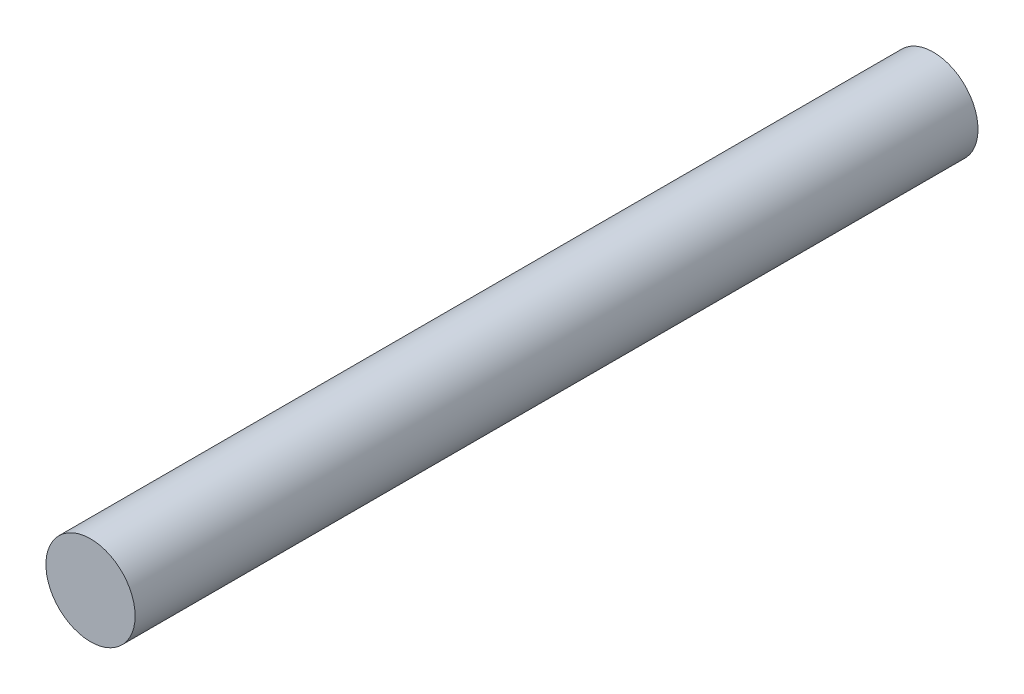
SolidWorks part; units mm, degrees
ref_plane "Alzado" through (0, 0, 0) normal (0, 0, 1) x (1, 0, 0)
ref_plane "Planta" through (0, 0, 0) normal (0, 1, 0) x (1, 0, 0)
ref_plane "Vista lateral" through (0, 0, 0) normal (1, 0, 0) x (0, 0, -1)
sketch "Croquis1" plane through (0, 0, 0) normal (0, 0, 1) x (1, 0, 0)
  circle A0 centre (0, 0) radius 7.9375
  dimension "D1" = 15.875
extrude "Saliente-Extruir1" add sketch "Croquis1" along normal mid plane 150
